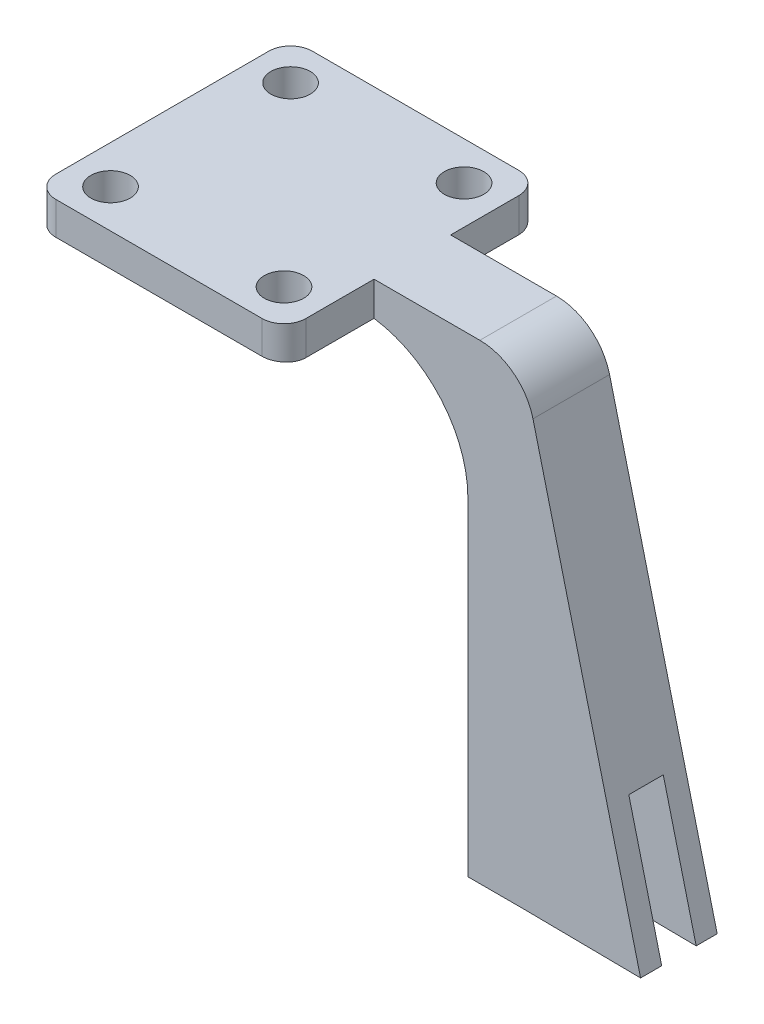
SolidWorks part; units mm, degrees
ref_plane "Front Plane" through (0, 0, 0) normal (0, 0, 1) x (1, 0, 0)
ref_plane "Top Plane" through (0, 0, 0) normal (0, 1, 0) x (1, 0, 0)
ref_plane "Right Plane" through (0, 0, 0) normal (1, 0, 0) x (0, 0, -1)
sketch "Sketch1" plane through (0, 0, 0) normal (0, 1, 0) x (1, 0, 0)
  line L5 (-9.425, -11.725) -> (9.425, -11.725)
  line L6 (-11.425, -9.725) -> (-11.425, 9.725)
  line L7 (-9.425, 11.725) -> (9.425, 11.725)
  line L8 (11.425, -9.725) -> (11.425, 9.725)
  circle A0 centre (-7.925, 8.225) radius 1.8
  arc A1 (-9.425, -11.725) -> (-11.425, -9.725) centre (-9.425, -9.725) cw
  arc A2 (9.425, -11.725) -> (11.425, -9.725) centre (9.425, -9.725) ccw
  arc A3 (9.425, 11.725) -> (11.425, 9.725) centre (9.425, 9.725) cw
  arc A4 (-11.425, 9.725) -> (-9.425, 11.725) centre (-9.425, 9.725) cw
  point P0 (0, 0)
  point P1 (0, 0)
  point P13 (11.425, -11.725)
  point P16 (11.425, 11.725)
  point P19 (-11.425, 11.725)
  dimension "D3" = 3.5
  dimension "D4" = 3.5
  dimension "D5" = 2
  dimension "D1" = 22.85
  dimension "D2" = 23.45
extrude "Boss-Extrude1" add sketch "Sketch1" along normal blind 3
sketch "Sketch2" plane through (0, 3, 0) normal (0, 1, 0) x (1, 0, 0)
  line L0 (9.425, 11.725) -> (-9.425, 11.725) construction
  line L2 (11.425, -9.725) -> (11.425, 9.725) construction
  line L3 (-9.425, -11.725) -> (9.425, -11.725) construction
  line L4 (-11.425, 9.725) -> (-11.425, -9.725) construction
  circle A0 centre (7.925, 8.225) radius 1.8
  circle A1 centre (-7.925, -8.225) radius 1.8
  circle A2 centre (7.925, -8.225) radius 1.8
  dimension "D1" = 3.5
  dimension "D2" = 3.5
  dimension "D4" = 3.5
  dimension "D6" = 3.5
  dimension "D3" = 3.5
  dimension "D5" = 3.5
extrude "Cut-Extrude1" cut sketch "Sketch2" against normal through all
sketch "Sketch3" plane through (0, 3, 0) normal (0, 1, 0) x (1, 0, 0)
  line L1 (0, 3.5) -> (25, 3.5)
  line L2 (0, 3.5) -> (0, -3.5)
  line L3 (0, -3.5) -> (25, -3.5)
  line L4 (25, 3.5) -> (25, -3.5)
  dimension "D1" = 25
  dimension "D2" = 7
  dimension "D3" = 3.5
extrude "Boss-Extrude2" add sketch "Sketch3" against normal blind 3
sketch "Sketch4" plane through (0, 0, 0) normal (0, -1, 0) x (1, 0, 0)
  line L0 (25, -3.5) -> (11.425, -3.5) construction
  line L1 (25, 3.5) -> (20, 3.5)
  line L2 (25, 3.5) -> (25, -3.5)
  line L3 (25, -3.5) -> (20, -3.5)
  line L4 (20, 3.5) -> (20, -3.5)
  dimension "D1" = 5
extrude "Boss-Extrude3" add sketch "Sketch4" along normal blind 40
sketch "Sketch7" plane through (0, 0, 3.5) normal (0, 0, 1) x (1, 0, 0)
  line L0 (25, 3) -> (35.7791, -40.1199)
  line L3 (25, 3) -> (25, -40)
  line L4 (25, -40) -> (35.7791, -40.1199)
extrude "Boss-Extrude4" add sketch "Sketch7" against normal blind 7
sketch "Sketch12" plane through (0, 0, 0) normal (0, 1, 0) x (1, 0, 0)
  line L0 (25, 3.5) -> (25, -3.5) construction
  line L1 (20, -3.5) -> (25, -3.5)
  line L2 (20, -3.5) -> (20, 3.5)
  line L3 (20, 3.5) -> (25, 3.5)
  line L4 (25, -3.5) -> (25, 3.5)
  line L5 (20, 3.5) -> (25, 3.5) construction
extrude "Boss-Extrude5" add sketch "Sketch12" along normal blind 2
fillet "Fillet1" radius 10 1 edges at (20, 0, 0)
fillet "Fillet2" radius 5 1 edges at (25, 3, 0)
ref_plane "Plane1" through (-0.4418, -39.717, 0) normal (-0.0111, -0.9999, 0) x (-0.9999, 0.0111, 0)
sketch "Sketch13" plane through (-0.4418, -39.717, 0) normal (-0.0111, -0.9999, 0) x (-0.9999, 0.0111, 0)
  line L1 (-19.7341, 1.581) -> (-38.1152, 1.581)
  line L2 (-19.7341, 1.581) -> (-19.7341, -1.569)
  line L3 (-19.7341, -1.569) -> (-38.1152, -1.569)
  line L4 (-38.1152, 1.581) -> (-38.1152, -1.569)
  line L5 (-19.7341, 1.581) -> (-38.1152, -1.569) construction
  line L6 (-19.7341, -1.569) -> (-38.1152, 1.581) construction
  point P0 (-28.9246, 0.006)
  dimension "D1" = 3.15
extrude "Cut-Extrude2" cut sketch "Sketch13" against normal blind 12
sketch "Sketch14" plane through (0, -40, 0) normal (0, -1, 0) x (1, 0, 0)
  line L0 (25, 3.5) -> (20, 3.5) construction
  line L1 (19.4427, -1.575) -> (25.5284, -1.575)
  line L2 (19.4427, -1.575) -> (19.4427, 1.575)
  line L3 (19.4427, 1.575) -> (25.5284, 1.575)
  line L4 (25.5284, -1.575) -> (25.5284, 1.575)
  line L5 (19.4427, -1.575) -> (25.5284, 1.575) construction
  line L6 (19.4427, 1.575) -> (25.5284, -1.575) construction
  point P0 (22.4856, 0)
  dimension "D1" = 3.15
  dimension "D2" = 3.5
extrude "Cut-Extrude3" cut sketch "Sketch14" against normal blind 11
